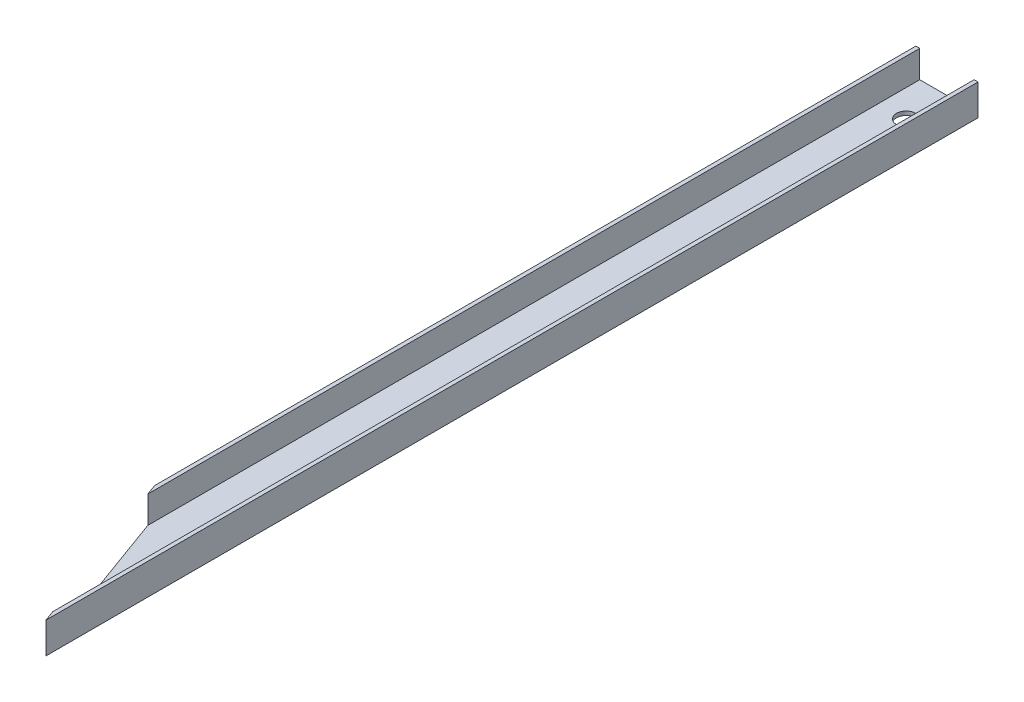
SolidWorks part; units mm, degrees
ref_plane "Front Plane" through (0, 0, 0) normal (0, 0, 1) x (1, 0, 0)
ref_plane "Top Plane" through (0, 0, 0) normal (0, 1, 0) x (1, 0, 0)
ref_plane "Right Plane" through (0, 0, 0) normal (1, 0, 0) x (0, 0, -1)
sketch "Sketch1" plane through (0, 0, 0) normal (0, 0, 1) x (1, 0, 0)
  line L0 (-22.225, -9.525) -> (-22.225, 12.7)
  line L1 (-25.4, -12.7) -> (25.4, -12.7)
  line L2 (-25.4, -12.7) -> (-25.4, 12.7)
  line L3 (-22.225, -9.525) -> (22.225, -9.525)
  line L4 (25.4, -12.7) -> (25.4, 12.7)
  line L5 (22.225, -9.525) -> (22.225, 12.7)
  line L6 (-25.4, 12.7) -> (-22.225, 12.7)
  line L7 (25.4, 12.7) -> (22.225, 12.7)
  dimension "D1" = 25.4
  dimension "D2" = 50.8
  dimension "D3" = 3.175
extrude "Boss-Extrude1" add sketch "Sketch1" along normal blind 762
sketch "Sketch2" plane through (0, -12.7, 0) normal (0, -1, 0) x (1, 0, 0)
  line L0 (25.4, 762) -> (-25.4, 622.4281)
  line L1 (-25.4, 762) -> (-25.4, 0) construction
  line L2 (-25.4, 622.4281) -> (-25.4, 762)
  line L3 (-25.4, 762) -> (25.4, 762)
  dimension "D1" = 70
extrude "Cut-Extrude1" cut sketch "Sketch2" against normal through all
sketch "Sketch3" plane through (0, -12.7, 0) normal (0, -1, 0) x (1, 0, 0)
  line L0 (0, 0) -> (0, 25.4) construction
  line L1 (-25.4, 0) -> (25.4, 0) construction
  circle A0 centre (0, 33.3375) radius 7.9375
  dimension "D1" = 25.4
extrude "Cut-Extrude2" cut sketch "Sketch3" against normal up to next
